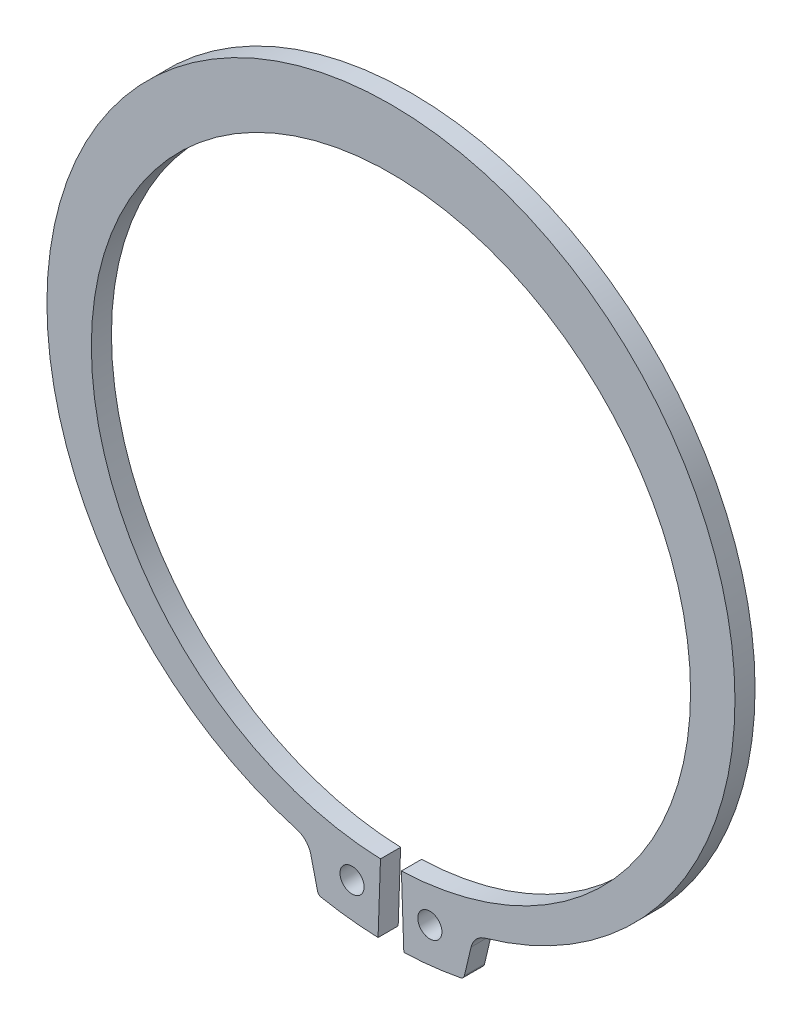
SolidWorks part; units mm, degrees
ref_plane "Front" through (0, 0, 0) normal (0, 0, 1) x (1, 0, 0)
ref_plane "Top" through (0, 0, 0) normal (0, 1, 0) x (1, 0, 0)
ref_plane "Right" through (0, 0, 0) normal (1, 0, 0) x (0, 0, -1)
sketch "Sketch1" plane through (0, 0, 0) normal (0, 0, 1) x (1, 0, 0)
  line L0 (0, 0) -> (-32.2594, -18.625) construction
  line L1 (0, 45.85) -> (0, -45.85) construction
  line L2 (-9.0419, -44.9781) -> (-10.3047, -39.6323) construction
  line L4 (-10.3047, -39.6323) -> (-11.2357, -43.2132) construction
  line L5 (-10.3047, -39.6323) -> (0, 0) construction
  line L6 (0, 37.25) -> (0, 44.65) construction
  line L7 (0, 44.65) -> (0, 40.95) construction
  line L8 (0, -37.25) -> (0, -45.85) construction
  line L9 (-5.3393, -45.5662) -> (0, 0) construction
  line L10 (0, 0) -> (-1.6011, -45.85) construction
  line L11 (-9.0419, -44.9781) -> (0, 0) construction
  line L12 (-9.9698, -41.0499) -> (-11.7123, -39.2573) construction
  line L13 (-10.841, -40.1536) -> (-10.3047, -39.6323) construction
  line L14 (-4.3352, -36.9969) -> (-5.3393, -45.5662) construction
  line L15 (-4.8373, -41.2815) -> (-3.3474, -41.4561) construction
  arc A0 (0, 44.65) -> (-10.3047, -39.6323) centre (0, 1.8789) ccw construction
  circle A2 centre (0, 0) radius 44.65 construction
  arc A3 (-9.0419, -44.9781) -> (-1.6011, -45.85) centre (0, 0) ccw construction
  circle A4 centre (0, 0) radius 37.25 construction
  circle A6 centre (-4.8373, -41.2815) radius 1.5 construction
  arc A7 (-11.7123, -39.2573) -> (-9.9698, -41.0499) centre (-12.3985, -41.6675) cw construction
  circle A9 centre (0, 0) radius 40 construction
  circle A10 centre (0, 0) radius 38.25 construction
  point P5 (-32.2594, -18.625)
  point P24 (-8.7999, -43.7743)
  point P35 (0, 44.65)
  point P36 (0, 37.25)
  point P37 (0, -37.25)
  point P38 (0, -45.85)
  dimension "Hole Diameter" = 3
  dimension "D10" = 2.506
  dimension "For OD" = 80
  dimension "ID" = 74.5
  dimension "Max Sec." = 7.4
  dimension "Lug Height" = 8.6
  dimension "D6" = 2
  dimension "D5" = 5.493
  dimension "D8" = 2.5
  dimension "D3" = 120
  dimension "D2" = 7.5
  dimension "D4" = 2.5
sketch "Sketch2" plane through (0, 0, 0) normal (-1, 0, 0) x (0, 1, 0)
  line L0 (-44.65, 1.25) -> (-44.65, -1.25) construction
  line L1 (44.65, -1.325) -> (44.65, 1.325) construction
  line L2 (0, 1.25) -> (0, -1.25) construction
  line L4 (-44.65, 0) -> (44.65, 0) construction
  point P3 (-44.65, 0)
  point P6 (0, 0)
  point P14 (44.65, 0)
  dimension "Thickness" = 2.5
  dimension "For Groove Width" = 2.65
sketch "Sketch4" plane through (0, 0, 0) normal (0, 0, 1) x (1, 0, 0)
  line L0 (-9.0419, -44.9781) -> (-10.3047, -39.6323) construction
  line L1 (-9.0419, -44.9781) -> (-10.3047, -39.6323)
  line L2 (0, 44.65) -> (0, 37.25)
  line L3 (-1.6011, -45.85) -> (-1.3, -37.2273)
  line L4 (0, 0) -> (-1.6011, -45.85) construction
  arc A0 (0, 44.65) -> (-10.3047, -39.6323) centre (0, 1.8789) ccw construction
  arc A1 (-9.0419, -44.9781) -> (-1.6011, -45.85) centre (0, 0) ccw construction
  circle A2 centre (-4.8373, -41.2815) radius 1.5 construction
  arc A4 (0, 44.65) -> (-10.3047, -39.6323) centre (0, 1.8789) ccw
  arc A5 (-9.0419, -44.9781) -> (-1.6011, -45.85) centre (0, 0) ccw
  circle A6 centre (-4.8373, -41.2815) radius 1.5
  circle A7 centre (0, 0) radius 37.25 construction
  arc A8 (0, 37.25) -> (-1.3, -37.2273) centre (0, 0) ccw
extrude "Boss-Extrude1" add sketch "Sketch4" along normal mid plane 2.5
fillet "Fillet1" radius 2.506 1 edges at (-10.3047, -39.6323, 0)
fillet "Fillet2" radius 0.6265 1 edges at (-9.0419, -44.9781, 0)
mirror "Mirror1" about plane through (0, 44.65, 1.25) normal (-1, 0, 0) of bodies 109
sketch "Sketch3" plane through (0, 0, 1.25) normal (0, 0, 1) x (1, 0, 0)
  line L0 (10.6946, -35.6817) -> (11.7127, -39.2572) construction
  line L1 (11.7127, -39.2572) -> (15.2881, -38.2391) construction
  line L2 (0, 44.65) -> (0, 37.25) construction
  circle A0 centre (0, 0) radius 37.25 construction
  arc A1 (11.7127, -39.2572) -> (-11.7127, -39.2572) centre (0, 1.8789) ccw construction
equation "\"D1@Fillet1\" = \"D10@Sketch1\""
equation "\"D1@Fillet2\" = \"D10@Sketch1\" / 4"
equation "\"Thickness@Boss-Extrude1\"  = \"Ring Thickness@Sketch5\""
equation "\"D2@Sketch1\"=\"Hole Diameter@Sketch1\"*2.5"
equation "\"D4@Sketch1\"=\"D2@Sketch1\"/3"
equation "\"D8@Sketch1\"=\"D4@Sketch1\""
